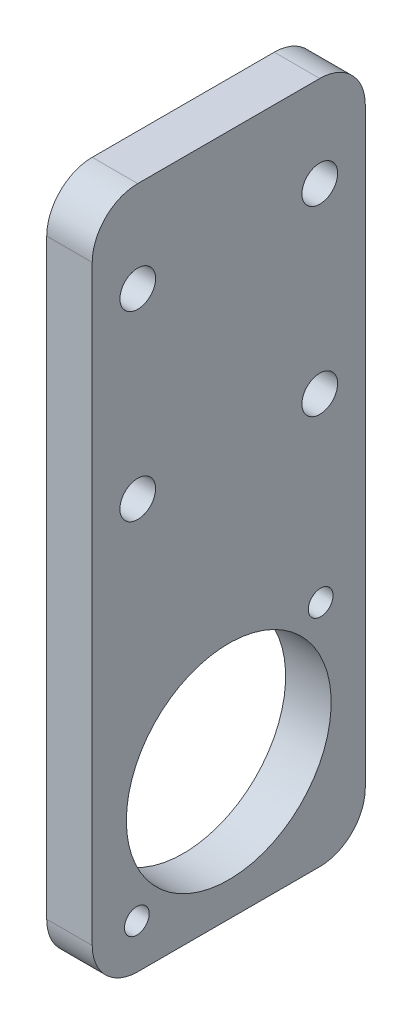
SolidWorks part; units mm, degrees
material "1060 Alloy"
ref_plane "Front Plane" through (0, 0, 0) normal (0, 0, 1) x (1, 0, 0)
ref_plane "Top Plane" through (0, 0, 0) normal (0, 1, 0) x (1, 0, 0)
ref_plane "Right Plane" through (0, 0, 0) normal (1, 0, 0) x (0, 0, -1)
ref_plane "Plane1" through (95.25, 0, 0) normal (1, 0, 0) x (0, 0, -1)
sketch "Sketch1" plane through (95.25, 0, 0) normal (1, 0, 0) x (0, 0, -1)
  line L0 (-184.15, -107.95) -> (-184.15, -25.4)
  line L1 (-190.5, -19.05) -> (-215.9, -19.05)
  line L2 (-222.25, -25.4) -> (-222.25, -107.95)
  line L3 (-215.9, -114.3) -> (-190.5, -114.3)
  circle A0 centre (-190.3762, -82.4262) radius 1.7272
  circle A1 centre (-216.0238, -108.0738) radius 1.7272
  circle A2 centre (-203.2, -95.25) radius 14.2875
  arc A3 (-184.15, -25.4) -> (-190.5, -19.05) centre (-190.5, -25.4) ccw
  arc A4 (-215.9, -19.05) -> (-222.25, -25.4) centre (-215.9, -25.4) ccw
  arc A5 (-222.25, -107.95) -> (-215.9, -114.3) centre (-215.9, -107.95) ccw
  arc A6 (-190.5, -114.3) -> (-184.15, -107.95) centre (-190.5, -107.95) ccw
  circle A7 centre (-215.9, -31.75) radius 2.4892
  circle A9 centre (-190.5, -31.75) radius 2.4892
  circle A10 centre (-215.9, -57.15) radius 2.4892
  circle A12 centre (-190.5, -57.15) radius 2.4892
extrude "Boss-Extrude1" add sketch "Sketch1" against normal blind 6.35
